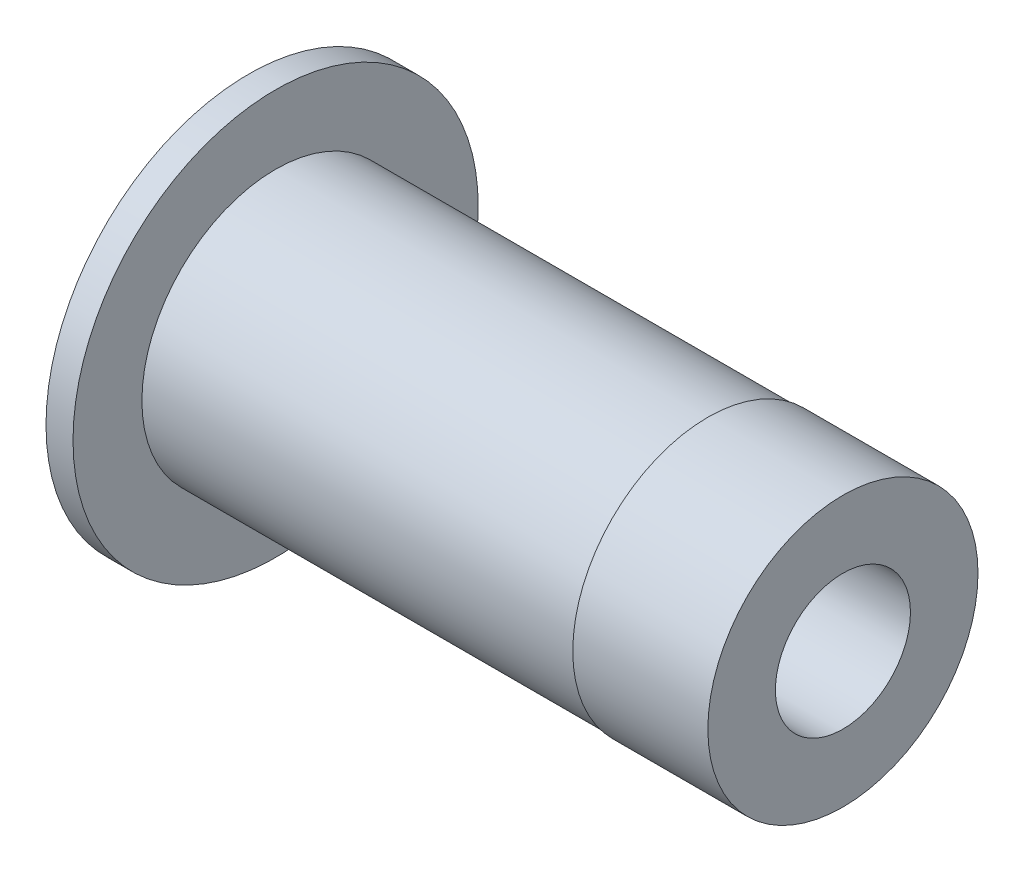
SolidWorks part; units mm, degrees
ref_plane "Front Plane" through (0, 0, 0) normal (0, 0, 1) x (1, 0, 0)
ref_plane "Top Plane" through (0, 0, 0) normal (0, 1, 0) x (1, 0, 0)
ref_plane "Right Plane" through (0, 0, 0) normal (1, 0, 0) x (0, 0, -1)
sketch "Sketch1" plane through (0, 0, 0) normal (1, 0, 0) x (0, 0, -1)
  circle A1 centre (0, 0) radius 9.9
  dimension "D2" = 19.8
extrude "Boss-Extrude1" add sketch "Sketch1" along normal blind 32
sketch "Sketch2" plane through (32, 0, 0) normal (1, 0, 0) x (0, 0, -1)
  circle A0 centre (0, 0) radius 10
  circle A2 centre (0, 0) radius 5
  dimension "D1" = 20
  dimension "D2" = 10
extrude "Boss-Extrude2" add sketch "Sketch2" along normal blind 10 separate body
sketch "Sketch3" plane through (0, 0, 0) normal (-1, 0, 0) x (0, 0, 1)
  circle A0 centre (0, 0) radius 15
extrude "Boss-Extrude3" add sketch "Sketch3" along normal blind 2
